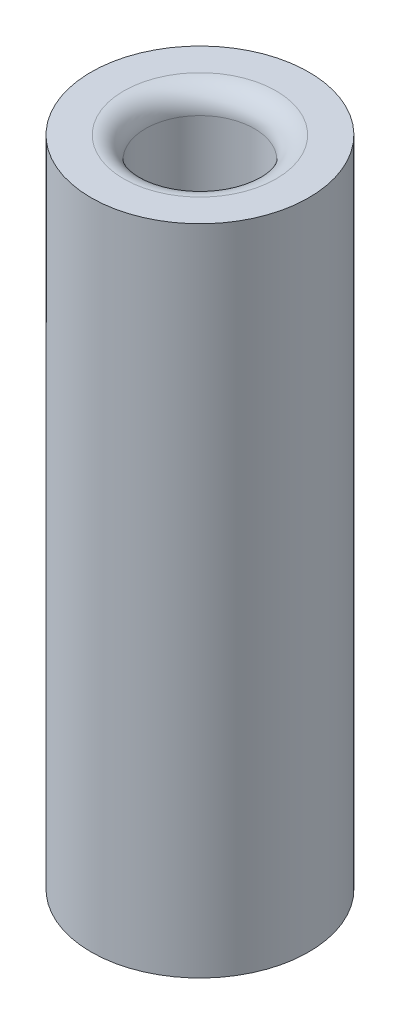
SolidWorks part; units mm, degrees
ref_plane "Front Plane" through (0, 0, 0) normal (0, 0, 1) x (1, 0, 0)
ref_plane "Top Plane" through (0, 0, 0) normal (0, 1, 0) x (1, 0, 0)
ref_plane "Right Plane" through (0, 0, 0) normal (1, 0, 0) x (0, 0, -1)
sketch "Sketch1" plane through (0, 0, 0) normal (0, 1, 0) x (1, 0, 0)
  circle A0 centre (0, 0) radius 2.5
  circle A1 centre (0, 0) radius 1.25
  dimension "D1" = 2.5
  dimension "D2" = 5
extrude "Boss-Extrude1" add sketch "Sketch1" along normal blind 15
fillet "Fillet1" radius 0.5 2 edges at (0, 0, 1.25) (0, 15, 1.25)
